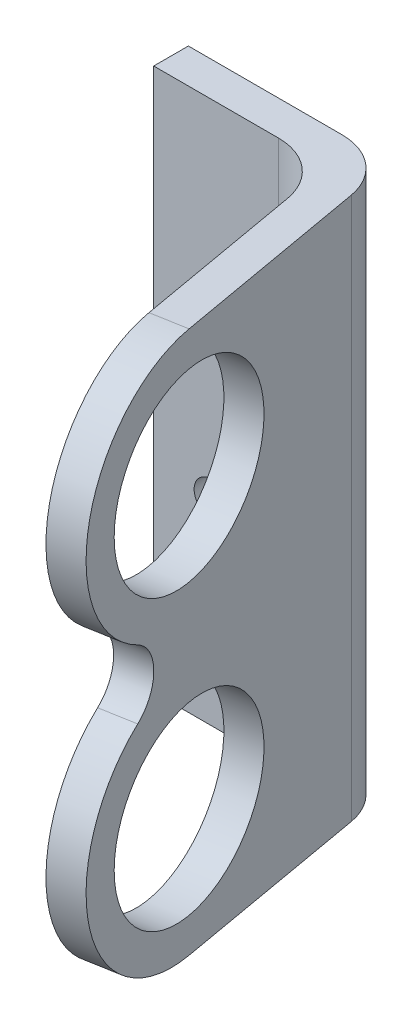
SolidWorks part; units mm, degrees
material "Acrylic (Medium-high impact)"
ref_plane "Front Plane" through (0, 0, 0) normal (0, 0, 1) x (1, 0, 0)
ref_plane "Top Plane" through (0, 0, 0) normal (0, 1, 0) x (1, 0, 0)
ref_plane "Right Plane" through (0, 0, 0) normal (1, 0, 0) x (0, 0, -1)
sketch "Sketch1" plane through (0, 0, 0) normal (0, 1, 0) x (1, 0, 0)
  line L0 (-2.3206, 10.9135) -> (11.0012, 10.9135)
  line L1 (15.9252, 6.7817) -> (20.8433, -21.1098)
  line L2 (20.8433, -21.1098) -> (17.8888, -21.6308)
  line L3 (17.8888, -21.6308) -> (13.4079, 3.7817)
  line L4 (8.4839, 7.9135) -> (-2.3206, 7.9135)
  line L5 (-2.3206, 7.9135) -> (-2.3206, 10.9135)
  arc A0 (15.9252, 6.7817) -> (11.0012, 10.9135) centre (11.0012, 5.9135) ccw
  arc A1 (13.4079, 3.7817) -> (8.4839, 7.9135) centre (8.4839, 2.9135) ccw
  dimension "D5" = 5
  dimension "D1" = 3
  dimension "D2" = 100
extrude "Boss-Extrude1" add sketch "Sketch1" along normal blind 47
sketch "Sketch2" plane through (0, 0, -7.9135) normal (0, 0, 1) x (1, 0, 0)
  line L0 (-2.3206, 47) -> (-2.3206, 0) construction
  line L1 (2.6794, 30) -> (2.6794, 47) construction
  line L2 (-2.3206, 47) -> (8.4839, 47) construction
  line L3 (2.6794, 17) -> (2.6794, 0) construction
  line L4 (-2.3206, 0) -> (8.4839, 0) construction
  circle A0 centre (2.6794, 30) radius 1.5
  circle A1 centre (2.6794, 17) radius 1.5
  dimension "D2" = 3
  dimension "D1" = 5
  dimension "D3" = 13
extrude "Cut-Extrude1" cut sketch "Sketch2" against normal through all
sketch "Sketch3" plane through (13.6504, 0, -2.4069) normal (-0.9848, 0, 0.1736) x (0.1736, 0, 0.9848)
  line L0 (13.4085, 11) -> (13.4085, 0) construction
  line L1 (-1.396, 0) -> (24.4085, 0) construction
  line L2 (13.4085, 36) -> (13.4085, 47) construction
  line L3 (-1.396, 47) -> (24.4085, 47) construction
  line L4 (24.4085, 47) -> (24.4085, 0) construction
  line L5 (13.4085, 47) -> (24.4085, 47)
  line L6 (24.4085, 47) -> (24.4085, 36)
  line L7 (13.4085, 0) -> (24.4085, 0)
  line L8 (24.4085, 0) -> (24.4085, 11)
  circle A0 centre (13.4085, 36) radius 8
  circle A1 centre (13.4085, 11) radius 8
  circle A2 centre (13.4085, 36) radius 11
  circle A3 centre (13.4085, 11) radius 11
  arc A4 (18.8949, 20.5342) -> (18.8949, 26.4658) centre (20.6015, 23.5) cw
  line M3 (-1.396, 0) -> (24.4085, 0)
  line M4 (24.4085, 0) -> (24.4085, 47)
  line M5 (24.4085, 47) -> (-1.396, 47)
  dimension "D1" = 16
  dimension "D2" = 22
  dimension "D3" = 25
extrude "Cut-Extrude2" cut sketch "Sketch3" against normal through all contours A2 M4 M5 | A3 M3 M4 | A1 | A0 | A4 A3 A2 M4
